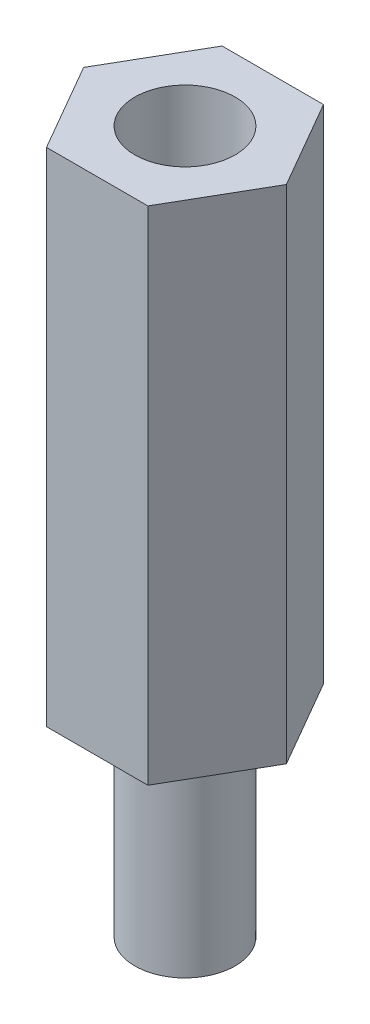
SolidWorks part; units mm, degrees
material "黄铜"
ref_plane "前视基准面" through (0, 0, 0) normal (0, 0, 1) x (1, 0, 0)
ref_plane "上视基准面" through (0, 0, 0) normal (0, 1, 0) x (1, 0, 0)
ref_plane "右视基准面" through (0, 0, 0) normal (1, 0, 0) x (0, 0, -1)
sketch "草图1" plane through (0, 0, 0) normal (0, 1, 0) x (1, 0, 0)
  line L1 (4.0415, 0) -> (2.0207, 3.5)
  line L2 (2.0207, 3.5) -> (-2.0207, 3.5)
  line L3 (-2.0207, 3.5) -> (-4.0415, 0)
  line L4 (-4.0415, 0) -> (-2.0207, -3.5)
  line L5 (-2.0207, -3.5) -> (2.0207, -3.5)
  line L6 (2.0207, -3.5) -> (4.0415, 0)
  circle A0 centre (0, 0) radius 2
  circle A1 centre (0, 0) radius 3.5 construction
  dimension "D1" = 4
  dimension "D2" = 7
extrude "凸台-拉伸1" add sketch "草图1" along normal blind 20
sketch "草图2" plane through (0, 0, 0) normal (0, -1, 0) x (1, 0, 0)
  circle A0 centre (0, 0) radius 2
  dimension "D1" = 4
extrude "凸台-拉伸2" add sketch "草图2" along normal blind 8 separate body
